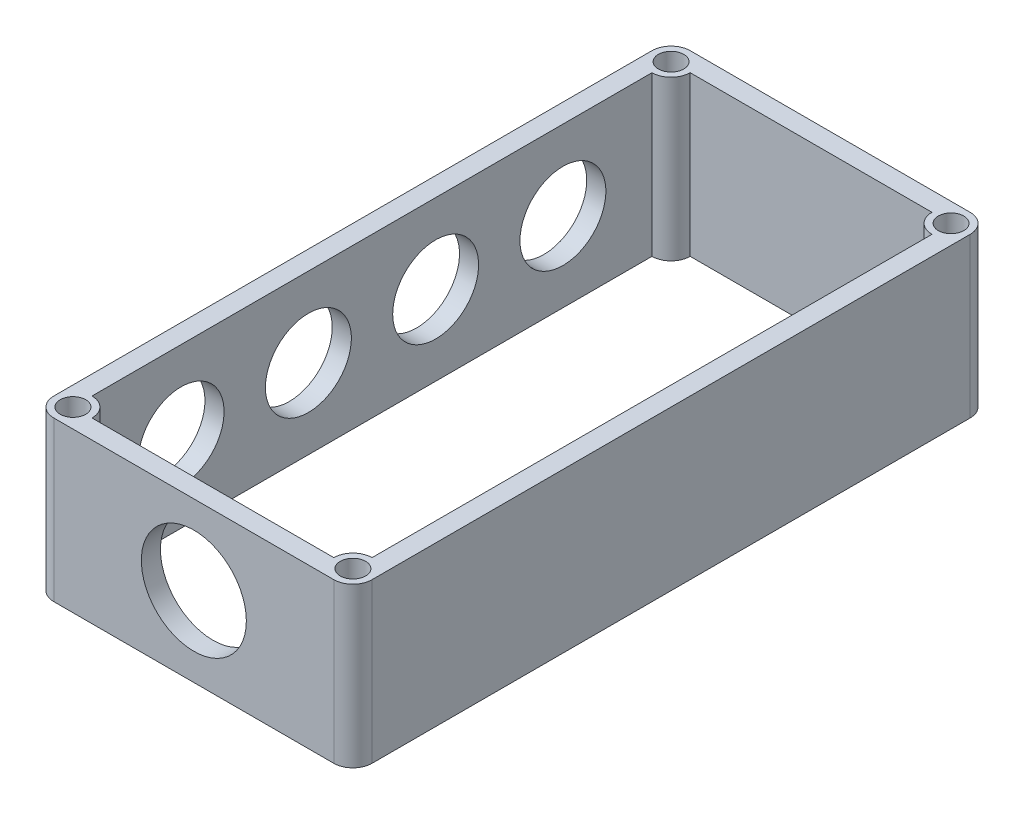
SolidWorks part; units mm, degrees
ref_plane "Front Plane" through (0, 0, 0) normal (0, 0, 1) x (1, 0, 0)
ref_plane "Top Plane" through (0, 0, 0) normal (0, 1, 0) x (1, 0, 0)
ref_plane "Right Plane" through (0, 0, 0) normal (1, 0, 0) x (0, 0, -1)
sketch "Sketch1" plane through (0, 0, 0) normal (0, 1, 0) x (1, 0, 0)
  line L1 (-22, -50) -> (22, -50)
  line L2 (-25, -47) -> (-25, 47)
  line L3 (-22, 50) -> (22, 50)
  line L4 (25, -47) -> (25, 47)
  line L5 (-25, -50) -> (25, 50) construction
  line L6 (-25, 50) -> (25, -50) construction
  line L7 (-22, -47) -> (22, -47)
  line L8 (-22, -47) -> (-22, 47)
  line L9 (-22, 47) -> (22, 47)
  line L10 (22, -47) -> (22, 47)
  line L11 (-22, -47) -> (22, 47) construction
  line L12 (-22, 47) -> (22, -47) construction
  arc A0 (-22, -50) -> (-25, -47) centre (-22, -47) cw
  arc A1 (22, -50) -> (25, -47) centre (22, -47) ccw
  arc A2 (22, 50) -> (25, 47) centre (22, 47) cw
  arc A3 (-25, 47) -> (-22, 50) centre (-22, 47) cw
  circle A4 centre (-22, 47) radius 2
  circle A5 centre (22, 47) radius 2
  circle A6 centre (22, -47) radius 2
  circle A7 centre (-22, -47) radius 2
  circle A8 centre (-22, 47) radius 3
  circle A9 centre (22, 47) radius 3
  circle A10 centre (22, -47) radius 3
  circle A11 centre (-22, -47) radius 3
  point P0 (0, 0)
  point P26 (0, 0)
  dimension "D3" = 3
  dimension "D4" = 4
  dimension "D1" = 100
  dimension "D2" = 50
extrude "Boss-Extrude1" add sketch "Sketch1" along normal blind 25 contours A9 L3 A8 L9 | L9 A8 A3 L8 A4 | L8 A8 L9 A4 | A11 L8 A8 L2 | L10 A9 A2 L9 A5 | L9 A9 L10 A5 | A10 L4 A9 L10 | A11 L1 A10 L7 | L7 A11 L8 A7 | A0 A11 L7 A7 L8 | A1 A10 L10 A6 L7 | L10 A10 L7 A6
sketch "Sketch2" plane through (0, 0, 50) normal (0, 0, 1) x (1, 0, 0)
  line L1 (-22, 25) -> (-22, 0) construction
  circle A0 centre (0, 12.5) radius 8.25
  point P4 (-29.7817, 8.1757)
  point P5 (-22, 12.5)
  point P6 (-22, 12.5)
  point P10 (0, 12.5)
  dimension "D1" = 16.5
extrude "Cut-Extrude1" cut sketch "Sketch2" against normal up to next
sketch "Sketch3" plane through (-25, 0, 0) normal (-1, 0, 0) x (0, 0, 1)
  line L0 (0, 0) -> (0, 25) construction
  line L1 (47, 25) -> (-47, 25) construction
  circle A0 centre (-30, 12.5) radius 6.75
  circle A3 centre (-10, 12.5) radius 6.75
  circle A4 centre (10, 12.5) radius 6.75
  circle A5 centre (30, 12.5) radius 6.75
  point P5 (0, 12.5)
  dimension "D2" = 13.5
  dimension "D1" = 20
  dimension "D3" = 20
extrude "Cut-Extrude2" cut sketch "Sketch3" against normal up to next
